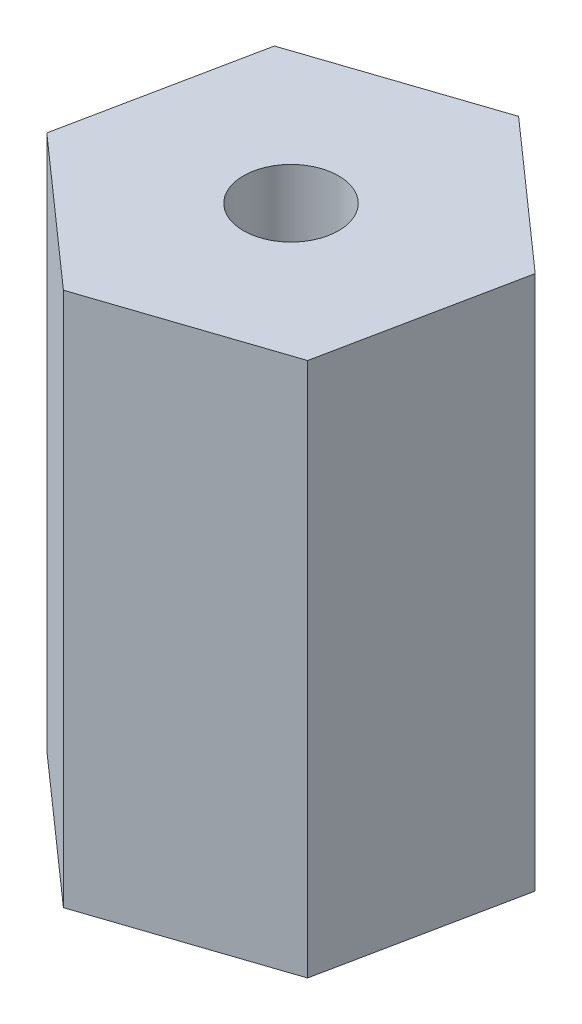
SolidWorks part; units mm, degrees
ref_plane "Front Plane" through (0, 0, 0) normal (0, 0, 1) x (1, 0, 0)
ref_plane "Top Plane" through (0, 0, 0) normal (0, 1, 0) x (1, 0, 0)
ref_plane "Right Plane" through (0, 0, 0) normal (1, 0, 0) x (0, 0, -1)
sketch "Sketch1" plane through (0, 0, 0) normal (0, 1, 0) x (1, 0, 0)
  line L1 (3.4315, -3.0374) -> (4.3462, 1.4531)
  line L2 (4.3462, 1.4531) -> (0.9147, 4.4905)
  line L3 (0.9147, 4.4905) -> (-3.4315, 3.0374)
  line L4 (-3.4315, 3.0374) -> (-4.3462, -1.4531)
  line L5 (-4.3462, -1.4531) -> (-0.9147, -4.4905)
  line L6 (-0.9147, -4.4905) -> (3.4315, -3.0374)
  circle A0 centre (0, 0) radius 3.9688 construction
  dimension "D1" = 7.9375
extrude "Boss-Extrude1" add sketch "Sketch1" along normal blind 12.7
hole_wizard "#4-40 Tapped Hole1" positions "Sketch2" profile "Sketch3" tap size "#4-40" standard "ANSI Inch"
sketch "Sketch2" plane through (0, 12.7, 0) normal (0, 1, 0) x (1, 0, 0)
  line L0 (-3.4315, 3.0374) -> (3.4315, -3.0374) construction
  point P7 (0, 0)
cosmetic thread "Hole Thread1"
sketch "Sketch3" plane through (0, 12.7, 0) normal (1, 0, 0) x (0, 0, 1)
  line L0 (0, 0) -> (0, 4.251)
  line L1 (0, 4.251) -> (1.1303, 3.5719)
  line L2 (1.1303, 3.5719) -> (1.1303, 0)
  line L5 (1.1303, 0) -> (0, 0)
  line L10 (0, 4.251) -> (-1.1303, 3.5719) construction
  line L11 (0, -6.35) -> (0, 107.95) construction
  dimension "Tap Drill Dia." = 2.2606
  dimension "Tap Drill Depth" = 3.5719
  dimension "Drill Angle" = 118
hole_wizard "#6-32 Tapped Hole1" positions "Sketch4" profile "Sketch5" tap size "#6-32" standard "ANSI Inch"
sketch "Sketch4" plane through (0, 0, 0) normal (0, -1, 0) x (-1, 0, 0)
  line L0 (-3.4315, -3.0374) -> (3.4315, 3.0374) construction
  point P7 (0, 0)
sketch "Sketch5" plane through (0, 0, 0) normal (1, 0, 0) x (0, 0, -1)
  line L0 (0, 0) -> (0, 4.3687)
  line L1 (0, 4.3687) -> (1.3525, 3.556)
  line L2 (1.3525, 3.556) -> (1.3525, 0)
  line L5 (1.3525, 0) -> (0, 0)
  line L10 (0, 4.3687) -> (-1.3525, 3.556) construction
  line L11 (0, -6.35) -> (0, 107.95) construction
  dimension "Tap Drill Dia." = 2.7051
  dimension "Tap Drill Depth" = 3.556
  dimension "Drill Angle" = 118
cosmetic thread "Hole Thread2"
